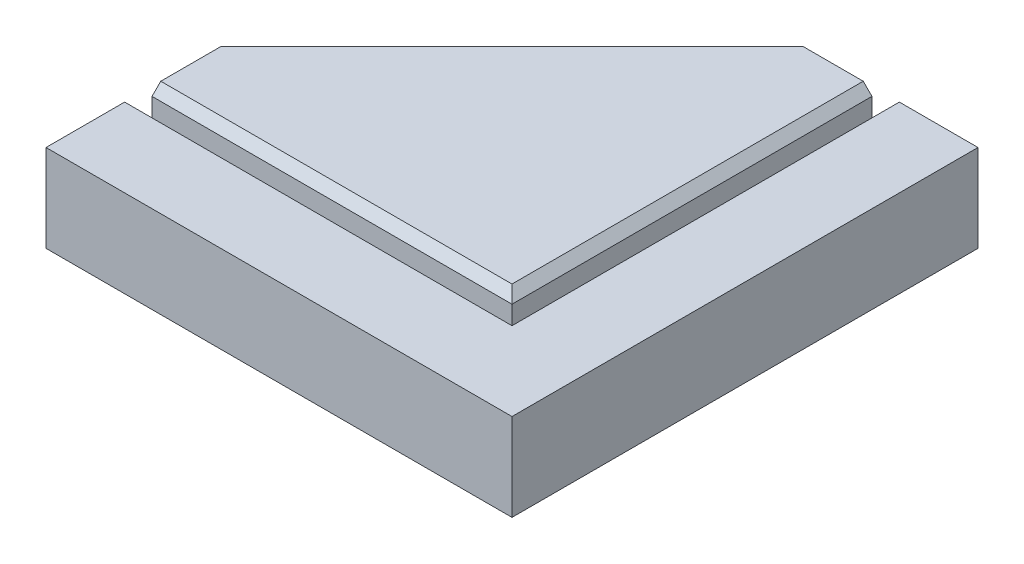
SolidWorks part; units mm, degrees
ref_plane "Front Plane" through (0, 0, 0) normal (0, 0, 1) x (1, 0, 0)
ref_plane "Top Plane" through (0, 0, 0) normal (0, 1, 0) x (1, 0, 0)
ref_plane "Right Plane" through (0, 0, 0) normal (1, 0, 0) x (0, 0, -1)
sketch "Sketch1" plane through (0, 0, 0) normal (0, 1, 0) x (1, 0, 0)
  line L1 (0, 0) -> (80, 0)
  line L2 (0, 0) -> (0, 80)
  line L3 (0, 80) -> (80, 80)
  line L4 (80, 0) -> (80, 80)
  dimension "D1" = 80
  dimension "D2" = 80
extrude "Boss-Extrude1" add sketch "Sketch1" along normal blind 15
sketch "Sketch2" plane through (0, 15, 0) normal (0, 1, 0) x (1, 0, 0)
  line L0 (80, 80) -> (0, 80) construction
  line L1 (15, 80) -> (18.2, 80)
  line L2 (15, 80) -> (15, 15)
  line L4 (18.2, 80) -> (18.2, 18.2)
  line L5 (80, 0) -> (80, 80) construction
  line L6 (18.2, 18.2) -> (80, 18.2)
  line L8 (15, 15) -> (80, 15)
  line L9 (80, 18.2) -> (80, 15)
  line L10 (0, 80) -> (0, 0) construction
  line L11 (0, 0) -> (80, 0) construction
  dimension "D1" = 3.2
  dimension "D2" = 3.2
  dimension "D3" = 15
  dimension "D4" = 15
extrude "Cut-Extrude1" [suppressed] cut sketch "Sketch2" against normal blind 8
chamfer "Chamfer1" [suppressed] distance 1.5 angle 45
sketch "Sketch3" plane through (0, 15, 0) normal (0, 1, 0) x (1, 0, 0)
  line L0 (80, 80) -> (0, 80) construction
  line L1 (65, 80) -> (61.8, 80)
  line L2 (65, 80) -> (65, 15)
  line L4 (61.8, 80) -> (61.8, 18.2)
  line L5 (0, 80) -> (0, 0) construction
  line L6 (61.8, 18.2) -> (0, 18.2)
  line L8 (65, 15) -> (0, 15)
  line L9 (0, 18.2) -> (0, 15)
  line L10 (80, 0) -> (80, 80) construction
  line L11 (0, 0) -> (80, 0) construction
  dimension "D1" = 15
  dimension "D2" = 15
  dimension "D3" = 3.2
  dimension "D4" = 3.2
extrude "Cut-Extrude2" cut sketch "Sketch3" against normal blind 8
chamfer "Chamfer3" distance 1.5 angle 45 4 edges at (32.5, 15, -15) (65, 15, -47.5) (61.8, 15, -49.1) (30.9, 15, -18.2)
sketch "Sketch4" plane through (0, 15, 0) normal (0, 1, 0) x (1, 0, 0)
  line L1 (0, 80) -> (50, 80)
  line L2 (0, 80) -> (0, 30)
  line L5 (50, 80) -> (0, 30)
  dimension "D1" = 50
  dimension "D2" = 50
extrude "Cut-Extrude3" cut sketch "Sketch4" against normal through all
sketch "Sketch5" [suppressed] plane through (0, 15, 0) normal (0, 1, 0) x (1, 0, 0)
  line L0 (80, 30) -> (30, 80)
  line L1 (80, 19.7) -> (80, 80) construction
  line L2 (80, 80) -> (19.7, 80) construction
  line L3 (30, 80) -> (80, 80)
  line L4 (80, 80) -> (80, 30)
  dimension "D1" = 50
  dimension "D2" = 50
extrude "Cut-Extrude4" [suppressed] cut sketch "Sketch5" against normal through all
sketch "Sketch6" [suppressed] plane through (0, 15, 0) normal (0, 1, 0) x (1, 0, 0)
  line L0 (80, 80) -> (80, 30)
  line L1 (80, 19.7) -> (80, 80) construction
  line L2 (80, 30) -> (30, 80)
  line L3 (80, 80) -> (21.7, 80) construction
  line L4 (30, 80) -> (80, 80)
  dimension "D1" = 50
  dimension "D2" = 50
extrude "Cut-Extrude5" [suppressed] cut sketch "Sketch6" against normal through all and the other way through all
sketch "Sketch7" [suppressed] plane through (0, 15, 0) normal (0, 1, 0) x (1, 0, 0)
  line L0 (0, 30) -> (50, 80)
  line L1 (0, 80) -> (0, 19.7) construction
  line L2 (58.3, 80) -> (0, 80) construction
  line L3 (50, 80) -> (0, 80)
  line L4 (0, 80) -> (0, 30)
  dimension "D1" = 50
  dimension "D2" = 50
extrude "Cut-Extrude6" [suppressed] cut sketch "Sketch7" against normal through all
equation "\"verticalDimension\"= 3.2"
equation "\"D1@Sketch2\"=\"verticalDimension\""
equation "\"horizontalDimension\"=3.2"
equation "\"D2@Sketch2\"=\"horizontalDimension\""
